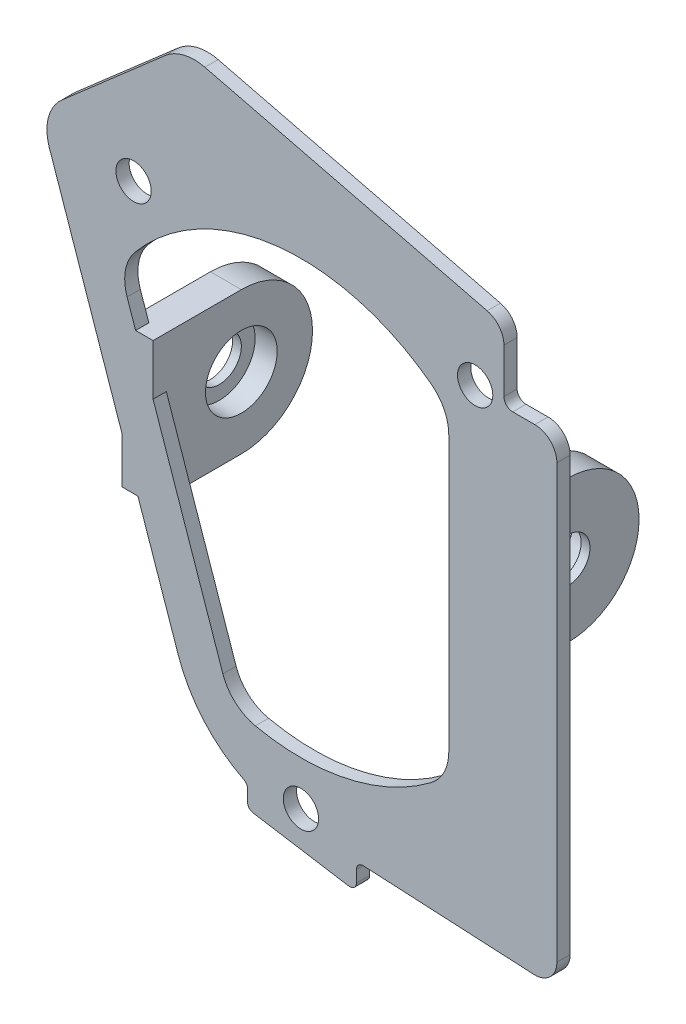
SolidWorks part; units mm, degrees
ref_plane "Front Plane" through (0, 0, 0) normal (0, 0, 1) x (1, 0, 0)
ref_plane "Top Plane" through (0, 0, 0) normal (0, 1, 0) x (1, 0, 0)
ref_plane "Right Plane" through (0, 0, 0) normal (1, 0, 0) x (0, 0, -1)
sketch "Sketch1" plane through (0, 0, 0) normal (0, 0, 1) x (1, 0, 0)
  line L0 (-37.9245, 45.1966) -> (0, 0) construction
  line L1 (0, 0) -> (0, 59) construction
  line L4 (33.5, 31.1247) -> (33.5, -31.1247)
  line L5 (-12.099, -61.1049) -> (-12.099, -63.7625)
  line L6 (-10.839, -65.2431) -> (10.839, -68.7569)
  line L7 (12.579, -67.2762) -> (12.579, -64.6187)
  line L8 (14.1566, -63.1207) -> (52.7412, -65.1207)
  line L9 (58, -60.1274) -> (58, 37.8793)
  line L10 (53, 42.8793) -> (48, 42.8793)
  line L11 (46, 44.8793) -> (46, 54.9649)
  line L12 (42.2, 59.8188) -> (-21.7544, 75.63)
  line L14 (-12.099, -60.1656) -> (-9.38, -61.4334) construction
  line L15 (-30.73, 73.4563) -> (-54.1355, 53.0287)
  line L16 (-57.0162, 42.2422) -> (-27.7893, -42.7336)
  line L17 (-39.3915, 21.7453) -> (-17.6816, -41.3752)
  line L18 (39.4787, 43.8455) -> (0, 0) construction
  circle A0 centre (0, 0) radius 59 construction
  arc A2 (29.5256, 39.1055) -> (-37.6109, 31.4074) centre (0, 0) ccw
  circle A3 centre (0, -59) radius 4
  circle A4 centre (-37.9245, 45.1966) radius 4
  circle A5 centre (39.4787, 43.8455) radius 4
  arc A6 (-27.7893, -42.7336) -> (-12.9238, -59.7655) centre (0.5796, -32.9763) ccw
  circle A7 centre (0, 0) radius 49 construction
  arc A9 (33.5, -31.1247) -> (29.5256, -39.1055) centre (23.5, -31.1247) cw
  arc A10 (33.5, 31.1247) -> (29.5256, 39.1055) centre (23.5, 31.1247) ccw
  arc A11 (-10.3343, -47.8978) -> (29.5256, -39.1055) centre (0, 0) ccw
  arc A12 (-17.6816, -41.3752) -> (-10.3343, -47.8978) centre (-8.2253, -38.1228) ccw
  arc A13 (-39.3915, 21.7453) -> (-37.6109, 31.4074) centre (-29.9352, 24.9977) cw
  arc A14 (-21.7544, 75.63) -> (-30.73, 73.4563) centre (-24.1544, 65.9222) ccw
  arc A15 (-54.1355, 53.0287) -> (-57.0162, 42.2422) centre (-47.5599, 45.4946) ccw
  arc A16 (58, 37.8793) -> (53, 42.8793) centre (53, 37.8793) ccw
  arc A17 (46, 54.9649) -> (42.2, 59.8188) centre (41, 54.9649) ccw
  arc A18 (48, 42.8793) -> (46, 44.8793) centre (48, 44.8793) cw
  arc A19 (52.7412, -65.1207) -> (58, -60.1274) centre (53, -60.1274) ccw
  arc A20 (12.579, -64.6187) -> (14.1566, -63.1207) centre (14.079, -64.6187) cw
  arc A21 (10.839, -68.7569) -> (12.579, -67.2762) centre (11.079, -67.2762) ccw
  arc A22 (-12.099, -63.7625) -> (-10.839, -65.2431) centre (-10.599, -63.7625) ccw
  arc A23 (-12.099, -61.1049) -> (-12.9238, -59.7655) centre (-13.599, -61.1049) ccw
  point P30 (0, -67)
  point P39 (-15.9806, -46.3209)
  point P44 (-26.808, 76.8793)
  point P47 (-59.2046, 48.6046)
  point P50 (58, 42.8793)
  point P53 (46, 58.8793)
  point P56 (46, 42.8793)
  point P59 (58, -65.3933)
  point P62 (12.579, -63.0389)
  point P65 (12.579, -69.0389)
  point P68 (-12.099, -65.0389)
  dimension "D1" = 118
  dimension "D4" = 8
  dimension "D8" = 58
  dimension "D9" = 10
  dimension "D18" = 30
  dimension "D23" = 10
  dimension "D24" = 10
  dimension "D25" = 5
  dimension "D26" = 2
  dimension "D27" = 5
  dimension "D28" = 1.5
  dimension "D5" = 40
  dimension "D6" = 6
  dimension "D7" = 33.5
  dimension "D2" = 25
  dimension "D10" = 12
  dimension "D11" = 108
  dimension "D12" = 8
  dimension "D13" = 4
  dimension "D14" = 16
  dimension "D15" = 18
  dimension "D16" = 3
  dimension "D17" = 65
  dimension "D19" = 75
  dimension "D20" = 43
  dimension "D21" = 125
  dimension "D22" = 10
  dimension "D29" = 2
  dimension "D30" = 42
  dimension "D3" = 10
extrude "Bumper link" add sketch "Sketch1" along normal blind 3
sketch "Sketch3" plane through (33.5, 0, 0) normal (-1, 0, 0) x (0, 0, 1)
  line L0 (3, 42.2422) -> (3, -42.7336) construction
  line L1 (-17, 16.125) -> (0, 16.125)
  line L2 (0, 42.2422) -> (0, -42.7336) construction
  line L3 (0, 16.125) -> (0, -16.125)
  line L4 (0, -16.125) -> (-17, -16.125)
  circle A0 centre (-17, 0) radius 8.125
  arc A1 (-17, 16.125) -> (-17, -16.125) centre (-17, 0) ccw
  circle A2 centre (-17, 0) radius 16.125 construction
  dimension "D1" = 16.25
  dimension "D2" = 20
  dimension "D3" = 8
extrude "Bearing block" add sketch "Sketch3" against normal blind 7
sketch "Sketch4" plane through (40.5, 0, 0) normal (1, 0, 0) x (0, 0, -1)
  circle A0 centre (17, 0) radius 8.125 construction
  circle A1 centre (17, 0) radius 8.125
  circle A2 centre (17, 0) radius 5
  dimension "D1" = 10
extrude "Bearing end flange" add sketch "Sketch4" against normal blind 2
mirror "Mirror1" about plane through (0, 0, 0) normal (1, 0, 0) of "Bearing end flange", "Bearing block"
sketch "Sketch6" plane through (0, 0, 0) normal (0, 0, 1) x (1, 0, 0)
  line L3 (-37.4584, 16.125) -> (-33.5, 4.616)
  line L4 (-33.5, 4.616) -> (-33.5, 16.125)
  line L5 (-33.5, 16.125) -> (-37.4584, 16.125)
  line L6 (-37.4584, 16.125) -> (-33.5, 4.616)
  line L7 (-33.5, 4.616) -> (-33.5, 16.125)
  line L8 (-33.5, 16.125) -> (-37.4584, 16.125)
  line L9 (-40.5, -16.125) -> (-36.9412, -16.125)
  line L10 (-36.9412, -16.125) -> (-40.5, -5.778)
  line L11 (-40.5, -5.778) -> (-40.5, -16.125)
  line L12 (-40.5, -16.125) -> (-36.9412, -16.125)
  line L13 (-36.9412, -16.125) -> (-40.5, -5.778)
  line L14 (-40.5, -5.778) -> (-40.5, -16.125)
  dimension "D1" = 0
  dimension "D2" = 0
extrude "Mirrored bearing block connection" add sketch "Sketch6" along normal up to surface (3 mm away) up to face at (-33.9245, 45.1966, 3)
